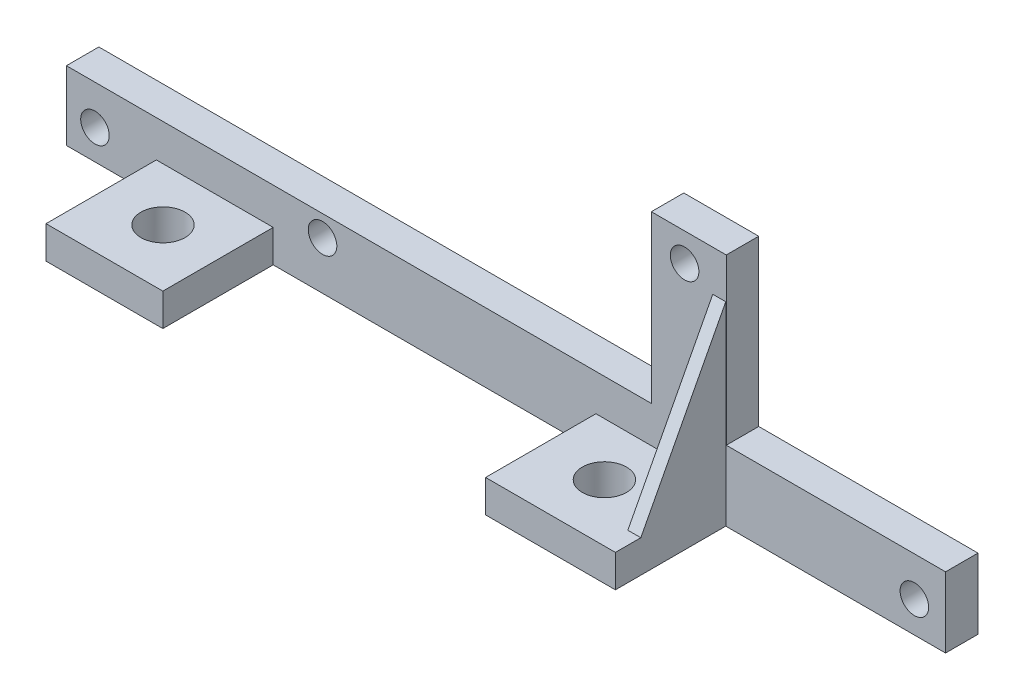
SolidWorks part; units mm, degrees
ref_plane "Front Plane" through (0, 0, 0) normal (0, 0, 1) x (1, 0, 0)
ref_plane "Top Plane" through (0, 0, 0) normal (0, 1, 0) x (1, 0, 0)
ref_plane "Right Plane" through (0, 0, 0) normal (1, 0, 0) x (0, 0, -1)
sketch "Sketch1" plane through (0, 0, 0) normal (0, 0, 1) x (1, 0, 0)
  line L1 (-43, 11.5) -> (43, 11.5)
  line L2 (-43, 11.5) -> (-43, -11.5)
  line L3 (-43, -11.5) -> (43, -11.5)
  line L4 (43, 11.5) -> (43, -11.5)
  point P0 (0, 0)
  dimension "D1" = 86
  dimension "D2" = 23
extrude "Boss-Extrude1" add sketch "Sketch1" against normal blind 3.175 contours L2 L1 L4 L3
ref_plane "Plane1" through (0, -11.5, 0) normal (0, -1, 0) x (-1, 0, 0)
sketch "Sketch3" plane through (0, -11.5, 0) normal (0, -1, 0) x (-1, 0, 0)
  line L0 (34.2, 0) -> (34.2, -10.795)
  line L1 (34.2, -10.795) -> (8.8, -10.795)
  line L2 (8.8, -10.795) -> (8.8, 0)
  line L3 (43, 0) -> (-43, 0) construction
  line L4 (34.2, 0) -> (8.8, 0)
  line L5 (0, 19.3889) -> (0, -14.044) construction
  line L6 (-34.2, 0) -> (-34.2, -10.795)
  line L7 (-34.2, -10.795) -> (-8.8, -10.795)
  line L8 (-8.8, -10.795) -> (-8.8, 0)
  line L9 (-34.2, 0) -> (-8.8, 0)
  line L10 (43, 3.175) -> (-43, 3.175) construction
  point P13 (21.5, 0)
  dimension "D2" = 13.97
  dimension "D3" = 21.5
extrude "Boss-Extrude2" add sketch "Sketch3" against normal blind 3.175
sketch "Sketch10" plane through (0, -11.5, 0) normal (0, -1, 0) x (1, 0, 0)
  line L0 (-21.5, 10.795) -> (-21.5, -3.175)
  line L1 (-8.8, 10.795) -> (-34.2, 10.795) construction
  line L2 (-43, -3.175) -> (43, -3.175) construction
ref_plane "Plane3" through (-21.5, 0, 0) normal (-1, 0, 0) x (0, 0, 1)
sketch "Sketch11" plane through (-21.5, 0, 0) normal (-1, 0, 0) x (0, 0, 1)
  line L0 (0, 7.5106) -> (8.3093, -8.325)
  line L1 (0, 11.5) -> (0, -11.5) construction
  line L2 (10.795, -8.325) -> (0, -8.325) construction
  point P6 (0, 0)
rib "Rib4" sketch "Sketch11" sketch "Sketch11" thickness 2.54 extrusion direction parallel to sketch draft on no parameters "D1"=2.54
sketch "Sketch13" plane through (0, 11.5, 0) normal (0, 1, 0) x (1, 0, 0)
  line L0 (0, 3.175) -> (0, 0)
  line L1 (-43, 3.175) -> (43, 3.175) construction
ref_plane "Plane4" through (0, 0, 0) normal (1, 0, 0) x (0, 0, -1)
mirror "Mirror1" about plane through (0, 0, 0) normal (1, 0, 0) of "Rib4"
ref_plane "Plane6" through (0, 11.5, 0) normal (0, 1, 0) x (1, 0, 0)
sketch "Sketch17" plane through (0, 11.5, 0) normal (0, 1, 0) x (1, 0, 0)
  line L0 (-22.77, 0) -> (-20.23, 0) construction
  line L2 (-21.5, 0) -> (-8.8, 0)
  line L7 (-21.5, 0) -> (-21.5, -10.795)
  line L8 (-21.5, -10.795) -> (-8.8, -10.795)
  line L9 (-8.8, 0) -> (-8.8, -10.795)
  line L10 (20.23, 0) -> (22.77, 0) construction
  line L11 (21.5, 0) -> (34.2, 0)
  line L12 (21.5, 0) -> (21.5, -10.795)
  line L13 (21.5, -10.795) -> (34.2, -10.795)
  line L14 (34.2, 0) -> (34.2, -10.795)
extrude "Cut-Extrude1" cut sketch "Sketch17" against normal through all
sketch "Sketch18" plane through (0, 11.5, 0) normal (0, 1, 0) x (1, 0, 0)
  circle A0 centre (-28.3737, -5.1774) radius 2.159
  circle A1 centre (14.8063, -5.1774) radius 2.159
  dimension "D1" = 4.318
  dimension "D2" = 43.18
extrude "Cut-Extrude2" cut sketch "Sketch18" against normal blind 127
sketch "Sketch19" plane through (0, 0, -3.175) normal (0, 0, -1) x (-1, 0, 0)
  line L0 (43, -11.5) -> (-43, -11.5) construction
  line L1 (43, 11.5) -> (43, -11.5) construction
  line L2 (-43, 11.5) -> (-43, -11.5) construction
  circle A0 centre (-39.952, -8.452) radius 1.397
  circle A1 centre (-17.473, 8.7438) radius 1.397
  circle A2 centre (17.9429, -6.801) radius 1.397
  circle A4 centre (40.206, -8.579) radius 1.397
  dimension "D1" = 2.794
  dimension "D2" = 2.921
  dimension "D3" = 2.794
  dimension "D4" = 25.0571
  dimension "D5" = 4.699
  dimension "D6" = 3.048
  dimension "D7" = 3.048
  dimension "D8" = 20.2438
  dimension "D9" = 25.527
extrude "Cut-Extrude3" cut sketch "Sketch19" against normal through all
sketch "Sketch20" plane through (0, 0, 0) normal (1, 0, 0) x (0, 0, -1)
sketch "Sketch21" plane through (0, 11.5, 0) normal (0, 1, 0) x (1, 0, 0)
  line L1 (-21.5, -10.795) -> (-22.77, -10.795)
  line L2 (-21.5, -10.795) -> (-21.5, 0)
  line L3 (-21.5, 0) -> (-22.77, 0)
  line L4 (-22.77, -10.795) -> (-22.77, 0)
extrude "Cut-Extrude4" cut sketch "Sketch21" against normal through all
sketch "Sketch23" plane through (0, 0, -3.175) normal (0, 0, -1) x (-1, 0, 0)
  line L0 (-14.2199, 11.5) -> (-14.2199, -4.7408)
  line L1 (13.0226, 11.5) -> (-13.0226, 11.5) construction
  line L2 (-14.2199, -4.7408) -> (43, -4.7408)
  line L3 (43, 11.5) -> (43, -11.5) construction
  line L4 (43, -4.7408) -> (43, 11.5)
  line L5 (43, 11.5) -> (-14.2199, 11.5)
  line L6 (-21.5497, 11.5) -> (-21.5497, -4.6178)
  line L7 (-21.5497, -4.6178) -> (-43, -4.6178)
  line L8 (-43, 11.5) -> (-43, -11.5) construction
  line L9 (-43, -4.6178) -> (-43, 11.5)
  line L10 (-43, 11.5) -> (-21.5497, 11.5)
extrude "Cut-Extrude5" cut sketch "Sketch23" against normal through all
